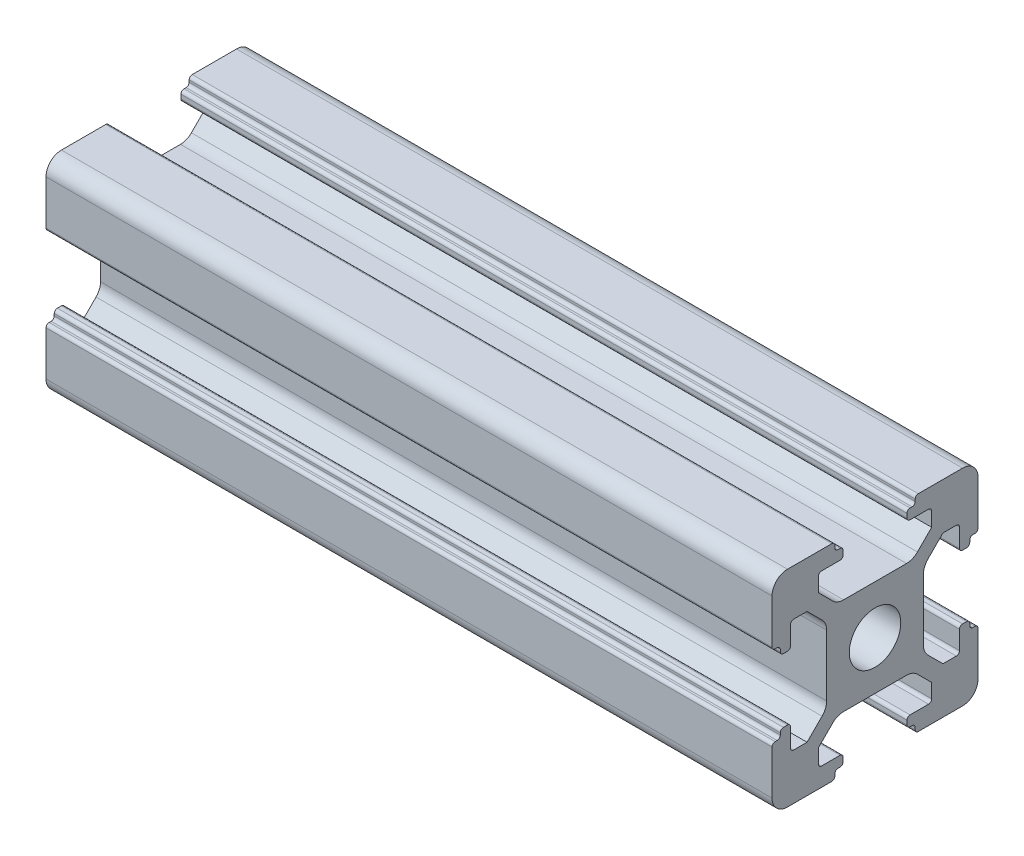
SolidWorks part; units mm, degrees
ref_plane "Front Plane" through (0, 0, 0) normal (0, 0, 1) x (1, 0, 0)
ref_plane "Top Plane" through (0, 0, 0) normal (0, 1, 0) x (1, 0, 0)
ref_plane "Right Plane" through (0, 0, 0) normal (1, 0, 0) x (0, 0, -1)
sketch "Sketch1" plane through (0, 0, 0) normal (1, 0, 0) x (0, 0, -1)
  line L0 (0, 0) -> (0, 50000) construction
  line L1 (0, 0) -> (-50000, 0) construction
  line L2 (10, 4.2) -> (10, 8.5)
  line L3 (9.7, 3.9) -> (9.5, 3.9)
  line L4 (9.2, 3.6) -> (9.2, 3.4)
  line L5 (8.9, 3.1) -> (8.5, 3.1)
  line L6 (8.2, 3.4) -> (8.2, 5.2)
  line L7 (7.9, 5.5) -> (6.6, 5.5)
  line L8 (6.6, 5.5) -> (5.1393, 4.0393)
  line L9 (8.5, 10) -> (4.2, 10)
  line L10 (3.9, 9.7) -> (3.9, 9.5)
  line L11 (3.6, 9.2) -> (3.4, 9.2)
  line L12 (3.1, 8.9) -> (3.1, 8.5)
  line L13 (3.4, 8.2) -> (5.2, 8.2)
  line L14 (5.5, 7.9) -> (5.5, 6.5213)
  line L15 (5.5, 6.5213) -> (4.118, 5.1393)
  line L16 (4.7, 2.9787) -> (4.7, -2.9787)
  line L17 (3.0574, 4.7) -> (-3.0574, 4.7)
  line L18 (-4.7, 2.9787) -> (-4.7, -2.9787)
  line L19 (-5.5, 6.5213) -> (-4.118, 5.1393)
  line L20 (-5.5, 7.9) -> (-5.5, 6.5213)
  line L21 (-3.4, 8.2) -> (-5.2, 8.2)
  line L22 (-3.1, 8.9) -> (-3.1, 8.5)
  line L23 (-3.6, 9.2) -> (-3.4, 9.2)
  line L24 (-3.9, 9.7) -> (-3.9, 9.5)
  line L25 (-8.5, 10) -> (-4.2, 10)
  line L26 (-6.6, 5.5) -> (-5.1393, 4.0393)
  line L27 (-7.9, 5.5) -> (-6.6, 5.5)
  line L28 (-8.2, 3.4) -> (-8.2, 5.2)
  line L29 (-8.9, 3.1) -> (-8.5, 3.1)
  line L30 (-9.2, 3.6) -> (-9.2, 3.4)
  line L31 (-9.7, 3.9) -> (-9.5, 3.9)
  line L32 (-10, 4.2) -> (-10, 8.5)
  line L33 (-10, -4.2) -> (-10, -8.5)
  line L34 (-9.7, -3.9) -> (-9.5, -3.9)
  line L35 (-9.2, -3.6) -> (-9.2, -3.4)
  line L36 (-8.9, -3.1) -> (-8.5, -3.1)
  line L37 (-8.2, -3.4) -> (-8.2, -5.2)
  line L38 (-7.9, -5.5) -> (-6.6, -5.5)
  line L39 (-6.6, -5.5) -> (-5.1393, -4.0393)
  line L40 (-8.5, -10) -> (-4.2, -10)
  line L41 (-3.9, -9.7) -> (-3.9, -9.5)
  line L42 (-3.6, -9.2) -> (-3.4, -9.2)
  line L43 (-3.1, -8.9) -> (-3.1, -8.5)
  line L44 (-3.4, -8.2) -> (-5.2, -8.2)
  line L45 (-5.5, -7.9) -> (-5.5, -6.5213)
  line L46 (-5.5, -6.5213) -> (-4.118, -5.1393)
  line L47 (3.0574, -4.7) -> (-3.0574, -4.7)
  line L48 (5.5, -6.5213) -> (4.118, -5.1393)
  line L49 (5.5, -7.9) -> (5.5, -6.5213)
  line L50 (3.4, -8.2) -> (5.2, -8.2)
  line L51 (3.1, -8.9) -> (3.1, -8.5)
  line L52 (3.6, -9.2) -> (3.4, -9.2)
  line L53 (3.9, -9.7) -> (3.9, -9.5)
  line L54 (8.5, -10) -> (4.2, -10)
  line L55 (6.6, -5.5) -> (5.1393, -4.0393)
  line L56 (7.9, -5.5) -> (6.6, -5.5)
  line L57 (8.2, -3.4) -> (8.2, -5.2)
  line L58 (8.9, -3.1) -> (8.5, -3.1)
  line L59 (9.2, -3.6) -> (9.2, -3.4)
  line L60 (9.7, -3.9) -> (9.5, -3.9)
  line L61 (10, -4.2) -> (10, -8.5)
  circle A0 centre (0, 0) radius 2.5
  arc A1 (10, 8.5) -> (8.5, 10) centre (8.5, 8.5) ccw
  arc A2 (9.7, 3.9) -> (10, 4.2) centre (9.7, 4.2) ccw
  arc A3 (9.5, 3.9) -> (9.2, 3.6) centre (9.5, 3.6) ccw
  arc A4 (9.2, 3.4) -> (8.9, 3.1) centre (8.9, 3.4) cw
  arc A5 (8.5, 3.1) -> (8.2, 3.4) centre (8.5, 3.4) cw
  arc A6 (8.2, 5.2) -> (7.9, 5.5) centre (7.9, 5.2) ccw
  arc A7 (5.2, 8.2) -> (5.5, 7.9) centre (5.2, 7.9) cw
  arc A8 (3.1, 8.5) -> (3.4, 8.2) centre (3.4, 8.5) ccw
  arc A9 (3.4, 9.2) -> (3.1, 8.9) centre (3.4, 8.9) ccw
  arc A10 (4.2, 10) -> (3.9, 9.7) centre (4.2, 9.7) ccw
  arc A11 (3.9, 9.5) -> (3.6, 9.2) centre (3.6, 9.5) cw
  arc A12 (4.7, 2.9787) -> (5.1393, 4.0393) centre (6.2, 2.9787) cw
  arc A13 (3.0574, 4.7) -> (4.118, 5.1393) centre (3.0574, 6.2) ccw
  arc A14 (-3.0574, 4.7) -> (-4.118, 5.1393) centre (-3.0574, 6.2) cw
  arc A15 (-4.7, 2.9787) -> (-5.1393, 4.0393) centre (-6.2, 2.9787) ccw
  arc A16 (-3.9, 9.5) -> (-3.6, 9.2) centre (-3.6, 9.5) ccw
  arc A17 (-4.2, 10) -> (-3.9, 9.7) centre (-4.2, 9.7) cw
  arc A18 (-3.4, 9.2) -> (-3.1, 8.9) centre (-3.4, 8.9) cw
  arc A19 (-3.1, 8.5) -> (-3.4, 8.2) centre (-3.4, 8.5) cw
  arc A20 (-5.2, 8.2) -> (-5.5, 7.9) centre (-5.2, 7.9) ccw
  arc A21 (-8.2, 5.2) -> (-7.9, 5.5) centre (-7.9, 5.2) cw
  arc A22 (-8.5, 3.1) -> (-8.2, 3.4) centre (-8.5, 3.4) ccw
  arc A23 (-9.2, 3.4) -> (-8.9, 3.1) centre (-8.9, 3.4) ccw
  arc A24 (-9.5, 3.9) -> (-9.2, 3.6) centre (-9.5, 3.6) cw
  arc A25 (-9.7, 3.9) -> (-10, 4.2) centre (-9.7, 4.2) cw
  arc A26 (-10, 8.5) -> (-8.5, 10) centre (-8.5, 8.5) cw
  arc A27 (-10, -8.5) -> (-8.5, -10) centre (-8.5, -8.5) ccw
  arc A28 (-9.7, -3.9) -> (-10, -4.2) centre (-9.7, -4.2) ccw
  arc A29 (-9.5, -3.9) -> (-9.2, -3.6) centre (-9.5, -3.6) ccw
  arc A30 (-9.2, -3.4) -> (-8.9, -3.1) centre (-8.9, -3.4) cw
  arc A31 (-8.5, -3.1) -> (-8.2, -3.4) centre (-8.5, -3.4) cw
  arc A32 (-8.2, -5.2) -> (-7.9, -5.5) centre (-7.9, -5.2) ccw
  arc A33 (-5.2, -8.2) -> (-5.5, -7.9) centre (-5.2, -7.9) cw
  arc A34 (-3.1, -8.5) -> (-3.4, -8.2) centre (-3.4, -8.5) ccw
  arc A35 (-3.4, -9.2) -> (-3.1, -8.9) centre (-3.4, -8.9) ccw
  arc A36 (-4.2, -10) -> (-3.9, -9.7) centre (-4.2, -9.7) ccw
  arc A37 (-3.9, -9.5) -> (-3.6, -9.2) centre (-3.6, -9.5) cw
  arc A38 (-4.7, -2.9787) -> (-5.1393, -4.0393) centre (-6.2, -2.9787) cw
  arc A39 (-3.0574, -4.7) -> (-4.118, -5.1393) centre (-3.0574, -6.2) ccw
  arc A40 (3.0574, -4.7) -> (4.118, -5.1393) centre (3.0574, -6.2) cw
  arc A41 (4.7, -2.9787) -> (5.1393, -4.0393) centre (6.2, -2.9787) ccw
  arc A42 (3.9, -9.5) -> (3.6, -9.2) centre (3.6, -9.5) ccw
  arc A43 (4.2, -10) -> (3.9, -9.7) centre (4.2, -9.7) cw
  arc A44 (3.4, -9.2) -> (3.1, -8.9) centre (3.4, -8.9) cw
  arc A45 (3.1, -8.5) -> (3.4, -8.2) centre (3.4, -8.5) cw
  arc A46 (5.2, -8.2) -> (5.5, -7.9) centre (5.2, -7.9) ccw
  arc A47 (8.2, -5.2) -> (7.9, -5.5) centre (7.9, -5.2) cw
  arc A48 (8.5, -3.1) -> (8.2, -3.4) centre (8.5, -3.4) ccw
  arc A49 (9.2, -3.4) -> (8.9, -3.1) centre (8.9, -3.4) ccw
  arc A50 (9.5, -3.9) -> (9.2, -3.6) centre (9.5, -3.6) cw
  arc A51 (9.7, -3.9) -> (10, -4.2) centre (9.7, -4.2) cw
  arc A52 (10, -8.5) -> (8.5, -10) centre (8.5, -8.5) cw
  point P24 (10, 10)
  point P41 (3.1, 9.2)
  point P44 (3.9, 10)
  point P94 (4.7, 0)
  point P95 (0, 4.7)
  point P175 (0, -4.7)
  point P176 (-4.7, 0)
  dimension "D1" = 5
  dimension "D15" = 1.5
  dimension "D16" = 0.3
  dimension "D19" = 1.5
  dimension "D2" = 20
  dimension "D3" = 1.8
  dimension "D4" = 6.2
  dimension "D5" = 3.4
  dimension "D6" = 11
  dimension "D7" = 6.1
  dimension "D8" = 1.5
  dimension "D9" = 20
  dimension "D10" = 6.1
  dimension "D11" = 6.2
  dimension "D12" = 11
  dimension "D13" = 45
  dimension "D14" = 1.8
  dimension "D17" = 3.5
  dimension "D18" = 3.5
extrude "Boss-Extrude2" add sketch "Sketch1" along normal mid plane 70.5
